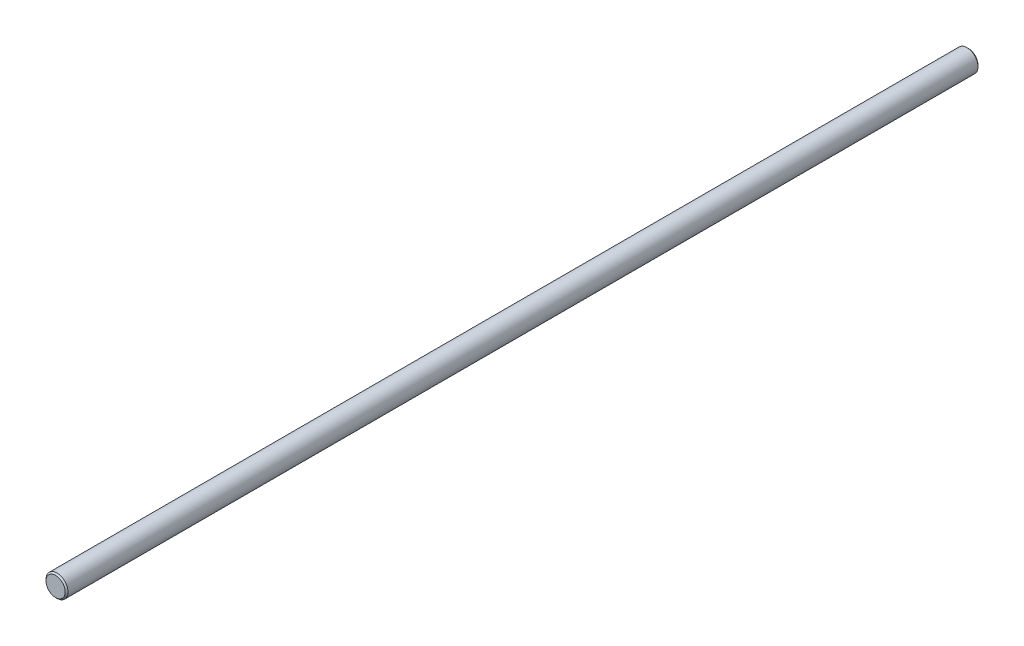
SolidWorks part; units mm, degrees
ref_plane "Alzado" through (0, 0, 0) normal (0, 0, 1) x (1, 0, 0)
ref_plane "Planta" through (0, 0, 0) normal (0, 1, 0) x (1, 0, 0)
ref_plane "Vista lateral" through (0, 0, 0) normal (1, 0, 0) x (0, 0, -1)
sketch "Croquis1" plane through (0, 0, 0) normal (0, 0, 1) x (1, 0, 0)
  circle A0 centre (0, 0) radius 4
  dimension "D1" = 8
extrude "Saliente-Extruir1" add sketch "Croquis1" along a picked direction on the side against the normal blind 332.2
chamfer "Chaflán1" distance 0.5 angle 45 2 edges at (4, 0, -332.2) (4, 0, 0)
